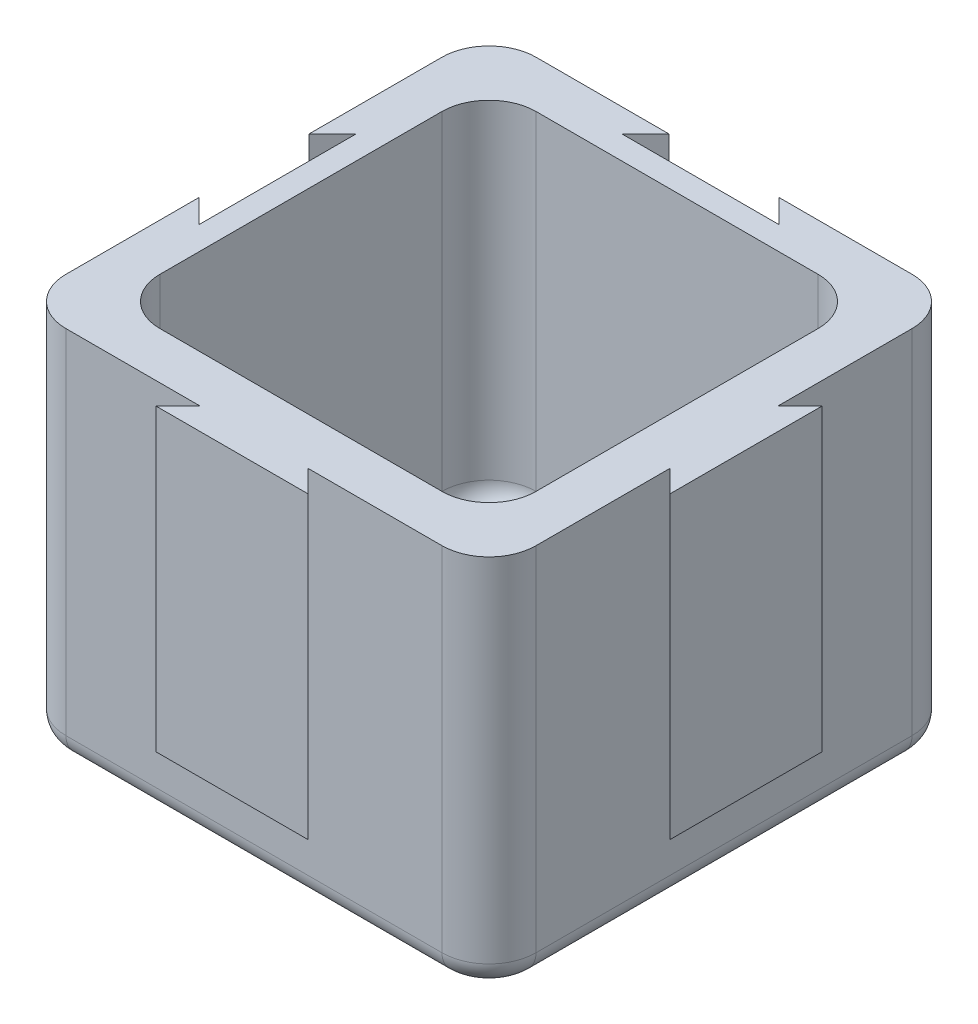
SolidWorks part; units mm, degrees
ref_plane "Front Plane" through (0, 0, 0) normal (0, 0, 1) x (1, 0, 0)
ref_plane "Top Plane" through (0, 0, 0) normal (0, 1, 0) x (1, 0, 0)
ref_plane "Right Plane" through (0, 0, 0) normal (1, 0, 0) x (0, 0, -1)
sketch "Sketch1" plane through (0, 0, 0) normal (0, 1, 0) x (1, 0, 0)
  line L1 (-50, 50) -> (50, 50)
  line L2 (-50, 50) -> (-50, -50)
  line L3 (-50, -50) -> (50, -50)
  line L4 (50, 50) -> (50, -50)
  line L5 (-50, 50) -> (50, -50) construction
  line L6 (-50, -50) -> (50, 50) construction
  point P0 (0, 0)
  dimension "D1" = 100
  dimension "D2" = 100
extrude "Boss-Extrude1" add sketch "Sketch1" along normal blind 80
shell "Shell1" thickness 10
sketch "Sketch2" plane through (0, 80, 0) normal (0, 1, 0) x (1, 0, 0)
  line L0 (-50, 45) -> (50, 45) construction
  line L1 (-50, 50) -> (-50, -50) construction
  line L2 (50, -50) -> (50, 50) construction
  line L3 (40, 40) -> (-40, 40) construction
  line L4 (-11.6667, 50) -> (-16.6667, 45)
  line L5 (50, 50) -> (-50, 50) construction
  line L6 (-16.6667, 45) -> (16.6667, 45)
  line L7 (16.6667, 45) -> (11.6667, 50)
  line L8 (-11.6667, 50) -> (11.6667, 50)
  point P14 (0, 45)
  dimension "D1" = 5
  dimension "D2" = 45
  dimension "D3" = 100
  dimension "D4" = 33.3333
extrude "Cut-Extrude1" cut sketch "Sketch2" against normal blind 64
sketch "Sketch3" plane through (0, 80, 0) normal (0, 1, 0) x (1, 0, 0)
  line L0 (-11.6667, -50) -> (-16.6667, -55) construction
  line L1 (-50, -50) -> (50, -50) construction
  line L2 (-16.6667, -55) -> (16.6667, -55) construction
  line L3 (16.6667, -55) -> (11.6667, -50) construction
  line L4 (11.6667, -50) -> (-11.6667, -50) construction
  line L5 (-50, -45) -> (50, -45) construction
  line L6 (-50, 50) -> (-50, -50) construction
  line L7 (50, -50) -> (50, 50) construction
  line L8 (-40, -40) -> (40, -40) construction
  line L9 (-11.4545, -50) -> (-16.1545, -54.7)
  line L10 (-11.4545, -50) -> (11.4545, -50)
  line L11 (-16.1545, -54.7) -> (16.1545, -54.7)
  line L12 (-11.5606, -50.1061) -> (-16.5606, -55.1061) construction
  line L14 (16.1545, -54.7) -> (11.4545, -50)
  point P4 (0, -50)
  dimension "D3" = 100
  dimension "D4" = 33.3333
  dimension "D1" = 45
  dimension "D2" = 5
  dimension "D5" = 5
  dimension "D7" = 0.3
  dimension "D8" = 0.15
  dimension "D6" = 0.15
extrude "Boss-Extrude2" add sketch "Sketch3" against normal blind 63.7
sketch "Sketch4" plane through (0, 80, 0) normal (0, 1, 0) x (1, 0, 0)
  line L0 (-45, 50) -> (-45, -50) construction
  line L1 (-11.6667, 50) -> (-50, 50) construction
  line L2 (-50, -50) -> (-11.4545, -50) construction
  line L3 (-40, 40) -> (-40, -40) construction
  line L4 (-45, 16.6667) -> (-45, -16.6667)
  line L5 (-45, -16.6667) -> (-50, -11.6667)
  line L6 (-50, 50) -> (-50, -50) construction
  line L7 (-50, -11.6667) -> (-50, 11.6667)
  line L8 (-50, 11.6667) -> (-45, 16.6667)
  point P14 (-45, 0)
  dimension "D1" = 5
  dimension "D2" = 45
  dimension "D3" = 33.3333
extrude "Cut-Extrude2" cut sketch "Sketch4" against normal blind 64
sketch "Sketch5" plane through (0, 80, 0) normal (0, 1, 0) x (1, 0, 0)
  line L0 (50, 11.6667) -> (50, -11.6667) construction
  line L1 (50, -50) -> (50, 50) construction
  line L2 (50, -11.6667) -> (55, -16.6667) construction
  line L3 (55, -16.6667) -> (55, 16.6667) construction
  line L4 (55, 16.6667) -> (50, 11.6667) construction
  line L5 (45, 50) -> (45, -50) construction
  line L6 (50, 50) -> (11.6667, 50) construction
  line L7 (11.4545, -50) -> (50, -50) construction
  line L8 (50, 11.4545) -> (50, -11.4545)
  line L9 (40, -40) -> (40, 40) construction
  line L10 (50, -11.4545) -> (54.7, -16.1545)
  line L12 (54.7, -16.1545) -> (54.7, 16.1545)
  line L13 (54.7, -16.6667) -> (54.7, 16.6667) construction
  line L14 (54.7, 16.1545) -> (50, 11.4545)
  line L15 (50.1061, -11.5606) -> (55.1061, -16.5606) construction
  point P14 (50, 0)
  dimension "D1" = 5
  dimension "D2" = 45
  dimension "D4" = 33.3333
  dimension "D3" = 5
  dimension "D7" = 0.15
  dimension "D5" = 0.15
  dimension "D6" = 0.3
extrude "Boss-Extrude3" add sketch "Sketch5" against normal up to surface (63.7 mm away) up to face at (0, 16.3, 52.35)
fillet "Fillet1" radius 10 8 edges at (40, 42.5, 40) (50, 40, 50) (50, 40, -50) (40, 42.5, -40) (-40, 42.5, -40) (-50, 40, -50) (-40, 42.5, 40) (-50, 40, 50)
fillet "Fillet2" radius 5 16 edges at (-47.0711, 0, -47.0711) (-50, 0, 0) (-47.0711, 0, 47.0711) (0, 0, 50) (47.0711, 0, 47.0711) (50, 0, 0) (47.0711, 0, -47.0711) (0, 0, -50) (37.0711, 5, 37.0711) (0, 5, 40) (-37.0711, 5, 37.0711) (-40, 5, 0) (-37.0711, 5, -37.0711) (0, 5, -40) (37.0711, 5, -37.0711) (40, 5, 0)
equation "\"x\" = 100"
equation "\"y\"= 100"
equation "\"h\"= 80"
equation "\"D1@Sketch1\"=\"x\""
equation "\"D2@Sketch1\"=\"y\""
equation "\"D4@Sketch2\"=\"x\"/3"
equation "\"D1@Cut-Extrude1\"=\"h\"*0.8"
equation "\"D5@Sketch3\"=\"D2@Sketch3\""
equation "\"Tolerance\"= 0.15"
equation "\"D6@Sketch3\"=\"Tolerance\""
equation "\"D7@Sketch3\"=\"Tolerance\"*2"
equation "\"D8@Sketch3\"=\"Tolerance\""
equation "\"D1@Boss-Extrude2\"=\"h\"*0.8 - (\"Tolerance\" * 2)"
equation "\"D4@Sketch3\"=\"x\"/3"
equation "\"D3@Sketch4\"=\"y\"/3"
equation "\"D1@Cut-Extrude2\"=\"h\"*0.8"
equation "\"D3@Sketch5\"=\"D1@Sketch5\""
equation "\"D4@Sketch5\"=\"y\"/3"
equation "\"D6@Sketch5\"=\"Tolerance\"*2"
equation "\"D5@Sketch5\"=\"Tolerance\""
equation "\"D7@Sketch5\"=\"Tolerance\""
equation "\"D1@Boss-Extrude1\"=\"h\""
